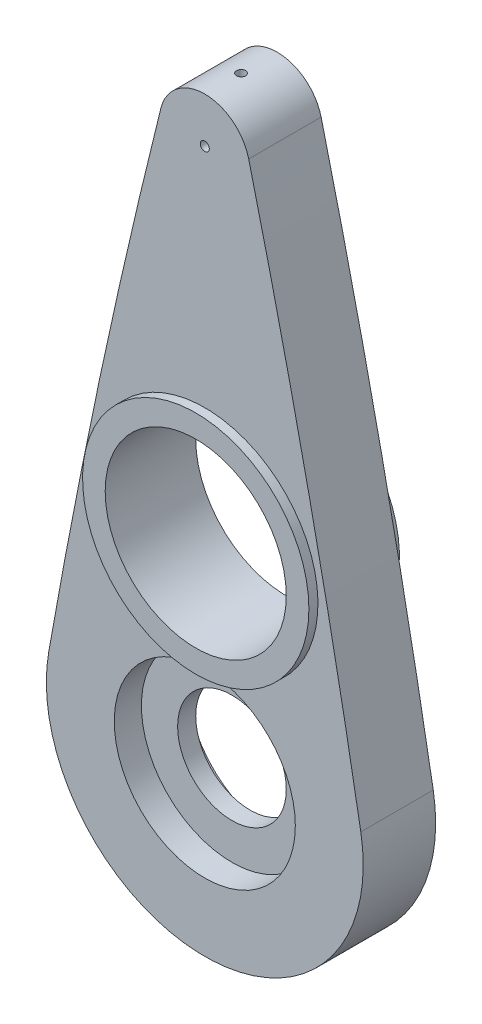
SolidWorks part; units mm, degrees
ref_plane "前视基准面" through (0, 0, 0) normal (0, 0, 1) x (1, 0, 0)
ref_plane "上视基准面" through (0, 0, 0) normal (0, 1, 0) x (1, 0, 0)
ref_plane "右视基准面" through (0, 0, 0) normal (1, 0, 0) x (0, 0, -1)
sketch "草图1" plane through (0, 0, 0) normal (0, 0, 1) x (1, 0, 0)
  line L0 (0, 60) -> (0, 0) construction
  line L1 (0, 0) -> (-17.2341, 3.0388) construction
  arc A0 (4.8508, 61.2125) -> (-4.8508, 61.2125) centre (0, 60) ccw
  arc A1 (-4.8508, 61.2125) -> (-17.2341, 3.0388) centre (814.8134, -143.6736) ccw
  arc A2 (-17.2341, 3.0388) -> (17.2341, 3.0388) centre (0, 0) ccw
  arc A3 (4.8508, 61.2125) -> (17.2341, 3.0388) centre (-814.8134, -143.6736) cw
  circle A4 centre (0, 0) radius 6
  dimension "D1" = 10
  dimension "D2" = 35
  dimension "D5" = 12
  dimension "D3" = 60
  dimension "D4" = 80
extrude "凸台-拉伸2" add sketch "草图1" along normal blind 8
sketch "草图2" plane through (0, 0, 8) normal (0, 0, 1) x (1, 0, 0)
  circle A0 centre (0, 0) radius 10
  circle A1 centre (0, 0) radius 6
  circle A2 centre (0, 0) radius 6 construction
  dimension "D1" = 20
extrude "切除-拉伸1" cut sketch "草图2" against normal blind 3
sketch "草图3" plane through (0, 0, 0) normal (0, 0, -1) x (-1, 0, 0)
  circle A0 centre (0, 0) radius 6
  circle A1 centre (0, 0) radius 10
  dimension "D1" = 12
  dimension "D2" = 20
extrude "切除-拉伸2" cut sketch "草图3" against normal blind 3
sketch "草图5" plane through (0, 0, 0) normal (0, 0, -1) x (-1, 0, 0)
  circle A0 centre (0, 60) radius 0.5
  dimension "D1" = 1
extrude "切除-拉伸3" cut sketch "草图5" against normal through all
sketch "草图6" plane through (0, 0, 0) normal (0, 0, -1) x (-1, 0, 0)
  line L0 (0, 60) -> (0, 0) construction
  circle A0 centre (0, 22.5) radius 10
  dimension "D1" = 20
  dimension "D2" = 22.5
extrude "切除-拉伸4" cut sketch "草图6" against normal through all
sketch "草图7" plane through (0, 0, 0) normal (0, 0, -1) x (-1, 0, 0)
  circle A0 centre (0, 22.5) radius 10
  circle A1 centre (0, 22.5) radius 12.5
  circle A2 centre (0, 0) radius 10 construction
  dimension "D1" = 20
extrude "凸台-拉伸3" add sketch "草图7" along normal blind 1
sketch "草图8" plane through (0, 0, 8) normal (0, 0, 1) x (1, 0, 0)
  circle A0 centre (0, 22.5) radius 10
  circle A1 centre (0, 22.5) radius 12.5
  circle A2 centre (0, 0) radius 10 construction
  dimension "D1" = 20
extrude "凸台-拉伸4" add sketch "草图8" along normal blind 1
ref_plane "基准面1" through (0, 65, 0) normal (0, 1, 0) x (1, 0, 0)
sketch "草图10" plane through (0, 65, 0) normal (0, 1, 0) x (1, 0, 0)
  line L0 (-4.8508, 0) -> (4.8508, 0) construction
  circle A0 centre (0, -4) radius 0.5
  point P2 (0, 0)
  point P5 (0, 0)
  dimension "D1" = 1
  dimension "D2" = 4
extrude "切除-拉伸5" cut sketch "草图10" against normal up to next
